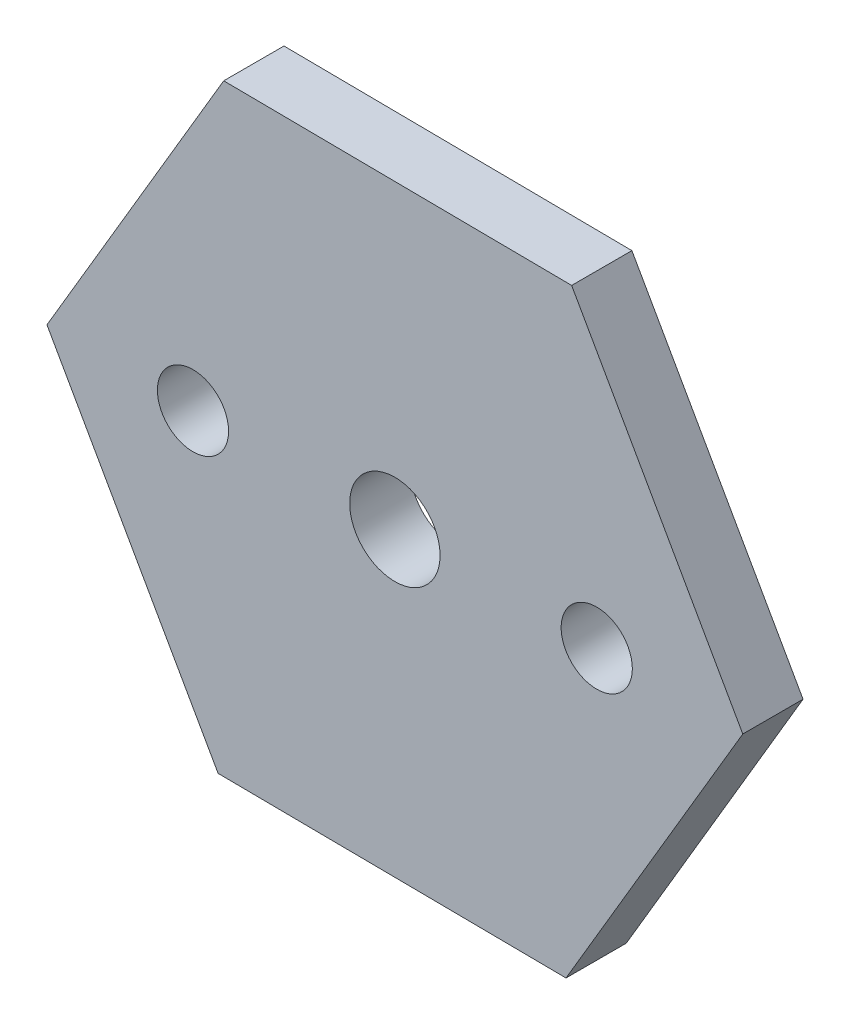
SolidWorks part; units mm, degrees
ref_plane "Front Plane" through (0, 0, 0) normal (0, 0, 1) x (1, 0, 0)
ref_plane "Top Plane" through (0, 0, 0) normal (0, 1, 0) x (1, 0, 0)
ref_plane "Right Plane" through (0, 0, 0) normal (1, 0, 0) x (0, 0, -1)
sketch "Sketch1" plane through (0, 0, 0) normal (0, 0, 1) x (1, 0, 0)
  line L0 (-14.6641, 0.1369) -> (14.6641, -0.1369) construction
  line L1 (-7.2135, 12.7679) -> (-14.6641, 0.1369)
  line L2 (-14.6641, 0.1369) -> (-7.4506, -12.631)
  line L3 (-7.4506, -12.631) -> (7.2135, -12.7679)
  line L4 (7.2135, -12.7679) -> (14.6641, -0.1369)
  line L5 (14.6641, -0.1369) -> (7.4506, 12.631)
  line L6 (7.4506, 12.631) -> (-7.2135, 12.7679)
  circle A0 centre (0, 0) radius 12.7 construction
  circle A1 centre (-8.509, 0.0794) radius 1.5
  circle A2 centre (8.509, -0.0794) radius 1.5
  circle A3 centre (0, 0) radius 1.905
  dimension "D2" = 3
  dimension "D3" = 3
  dimension "D6" = 3.81
  dimension "D1" = 25.4
  dimension "D4" = 8.509
  dimension "D5" = 8.509
extrude "Boss-Extrude1" add sketch "Sketch1" along normal blind 2.54
